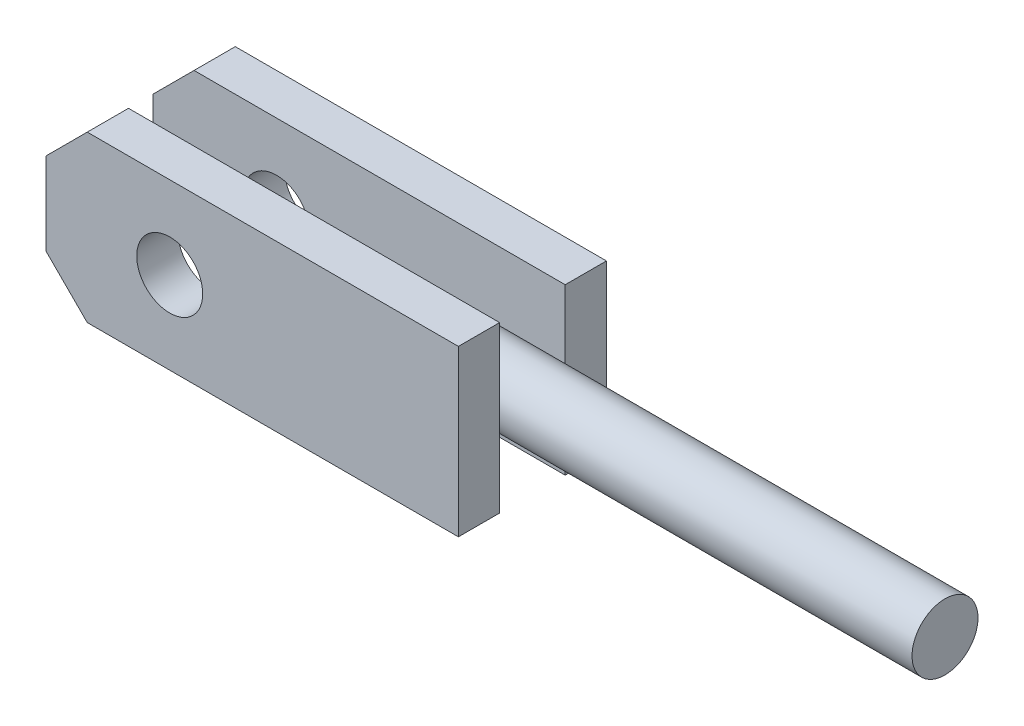
SolidWorks part; units mm, degrees
material "ASTM A36"
ref_plane "Front Plane" through (0, 0, 0) normal (0, 0, 1) x (1, 0, 0)
ref_plane "Top Plane" through (0, 0, 0) normal (0, 1, 0) x (1, 0, 0)
ref_plane "Right Plane" through (0, 0, 0) normal (1, 0, 0) x (0, 0, -1)
sketch "Sketch1" plane through (0, 0, 0) normal (0, 0, 1) x (1, 0, 0)
  line L1 (50, -20) -> (-50, -20)
  line L2 (50, -20) -> (50, 20)
  line L3 (50, 20) -> (-50, 20)
  line L4 (-50, -20) -> (-50, 20)
  line L5 (50, -20) -> (-50, 20) construction
  line L6 (50, 20) -> (-50, -20) construction
  point P0 (0, 0)
  dimension "D1" = 40
  dimension "D2" = 100
extrude "Boss-Extrude1" add sketch "Sketch1" along normal blind 10
sketch "Sketch4" plane through (0, 0, 10) normal (0, 0, 1) x (1, 0, 0)
  line L0 (-50, 20) -> (-50, -20) construction
  circle A0 centre (-20, 0) radius 8
  dimension "D2" = 16
  dimension "D1" = 30
extrude "Cut-Extrude1" cut sketch "Sketch4" against normal blind 10
chamfer "Chamfer2" distance 10 angle 45 1 edges at (-50, 20, 5)
chamfer "Chamfer3" distance 10 angle 45 1 edges at (-50, -20, 5)
sketch "Sketch5" plane through (50, 0, 0) normal (1, 0, 0) x (0, 0, -1)
  line L0 (0, -20) -> (0, 20) construction
  circle A0 centre (8, 0) radius 8
  dimension "D1" = 16
  dimension "D2" = 8
extrude "Boss-Extrude2" add sketch "Sketch5" along normal blind 100 and the other way blind 20 separate body
pattern_linear "LPattern1" count 2 spacing 25.9 along (0, 0, -1) of "Boss-Extrude1"
chamfer "Chamfer4" distance 10 angle 45 1 edges at (-50, 20, -20.9)
chamfer "Chamfer5" distance 10 angle 45 1 edges at (-50, -20, -20.9)
sketch "Sketch6" plane through (0, 0, -25.9) normal (0, 0, -1) x (-1, 0, 0)
  line L0 (50, 10) -> (50, -10) construction
  circle A0 centre (20, 0) radius 8
  dimension "D1" = 30
  dimension "D2" = 16
extrude "Cut-Extrude2" cut sketch "Sketch6" against normal blind 100
